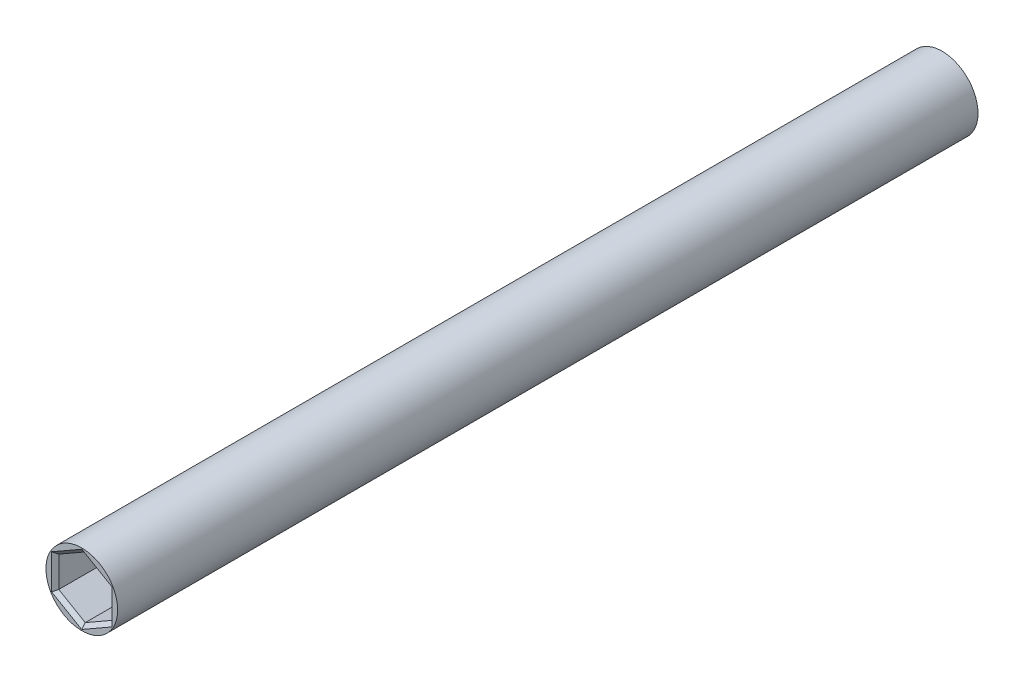
SolidWorks part; units mm, degrees
ref_plane "Front Plane" through (0, 0, 0) normal (0, 0, 1) x (1, 0, 0)
ref_plane "Top Plane" through (0, 0, 0) normal (0, 1, 0) x (1, 0, 0)
ref_plane "Right Plane" through (0, 0, 0) normal (1, 0, 0) x (0, 0, -1)
sketch "Sketch1" plane through (0, 0, 0) normal (0, 0, 1) x (1, 0, 0)
  circle A0 centre (0, 0) radius 0.5
  dimension "D1" = 1
extrude "Boss-Extrude1" add sketch "Sketch1" along normal blind 12
cosmetic thread "Cosmetic Thread1" parameters "D1"=3.2, "D2"=0.755
sketch "Sketch2" plane through (0, 0, 12) normal (0, 0, 1) x (1, 0, 0)
  line L1 (0.3695, -0.2152) -> (0.3712, 0.2124)
  line L2 (0.3712, 0.2124) -> (0.0016, 0.4277)
  line L3 (0.0016, 0.4277) -> (-0.3695, 0.2152)
  line L4 (-0.3695, 0.2152) -> (-0.3712, -0.2124)
  line L5 (-0.3712, -0.2124) -> (-0.0016, -0.4277)
  line L6 (-0.0016, -0.4277) -> (0.3695, -0.2152)
  circle A0 centre (0, 0) radius 0.3704 construction
extrude "Cut-Extrude1" cut sketch "Sketch2" against normal blind 1
chamfer "Chamfer1" distance 0.05 angle 45 6 edges at (0.3704, -0.0014, 12) (0.1864, 0.32, 12) (-0.184, 0.3215, 12) (-0.3704, 0.0014, 12) (-0.1864, -0.32, 12) (0.184, -0.3215, 12)
scale "Scale1" scale about centroid uniform scaling yes scale factor 1.9329
scale "Scale2" scale about centroid uniform scaling yes scale factor 1.5
